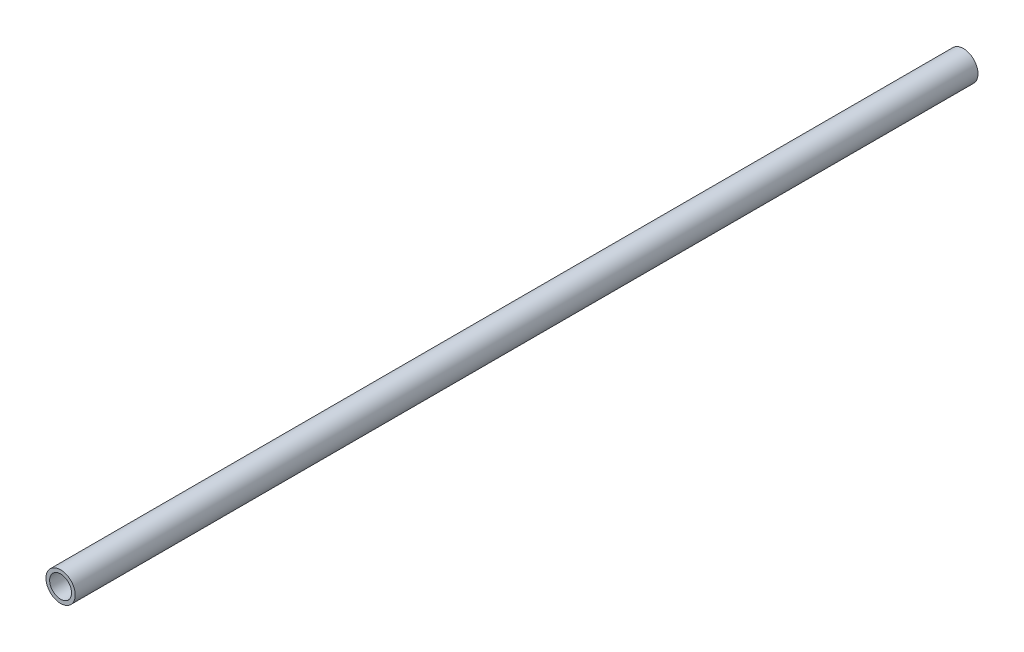
SolidWorks part; units mm, degrees
ref_plane "前视基准面" through (0, 0, 0) normal (0, 0, 1) x (1, 0, 0)
ref_plane "上视基准面" through (0, 0, 0) normal (0, 1, 0) x (1, 0, 0)
ref_plane "右视基准面" through (0, 0, 0) normal (1, 0, 0) x (0, 0, -1)
sketch "Model" plane through (0, 0, 0) normal (0, 0, 1) x (1, 0, 0)
  circle A0 centre (21.1445, 12.4911) radius 3
  circle A1 centre (21.1445, 12.4911) radius 4
extrude "凸台-拉伸1" add sketch "Model" along normal blind 247
